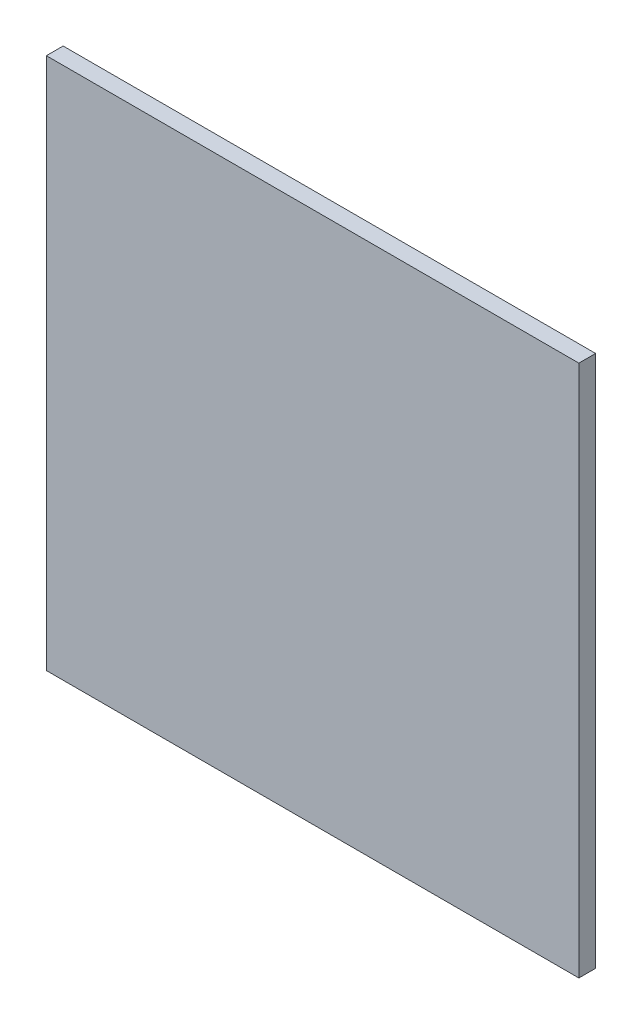
SolidWorks part; units mm, degrees
ref_plane "Front Plane" through (0, 0, 0) normal (0, 0, 1) x (1, 0, 0)
ref_plane "Top Plane" through (0, 0, 0) normal (0, 1, 0) x (1, 0, 0)
ref_plane "Right Plane" through (0, 0, 0) normal (1, 0, 0) x (0, 0, -1)
sketch "Sketch1" plane through (0, 0, 0) normal (0, 0, 1) x (1, 0, 0)
  line L1 (0, 0) -> (6.35, 0)
  line L2 (0, 0) -> (0, 6.35)
  line L3 (0, 6.35) -> (6.35, 6.35)
  line L4 (6.35, 0) -> (6.35, 6.35)
  dimension "D1" = 6.35
  dimension "D2" = 6.35
extrude "Boss-Extrude1" add sketch "Sketch1" along normal blind 0.2
